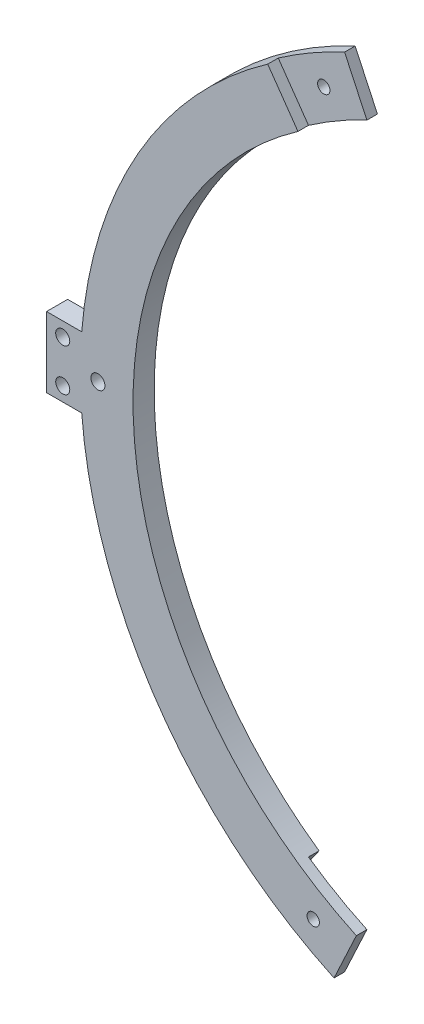
SolidWorks part; units mm, degrees
ref_plane "Plan de face" through (0, 0, 0) normal (0, 0, 1) x (1, 0, 0)
ref_plane "Plan de dessus" through (0, 0, 0) normal (0, 1, 0) x (1, 0, 0)
ref_plane "Plan de droite" through (0, 0, 0) normal (1, 0, 0) x (0, 0, -1)
sketch "Esquisse1" plane through (0, 0, 0) normal (0, 0, 1) x (1, 0, 0)
  line L0 (-130, -6) -> (-130, 6) construction
  line L1 (-120, 0) -> (-130, 0) construction
  line L2 (-134.5994, -10) -> (-124.5994, -10)
  line L3 (-124.5994, 10) -> (-134.5994, 10)
  line L4 (-134.5994, 10) -> (-134.5994, -10)
  line L5 (-124.5994, -10) -> (-124.5994, 10) construction
  line L6 (-130, 0) -> (0, 0) construction
  line L7 (-46.488, -99.6939) -> (-52.8273, -113.2885)
  line L8 (-46.488, 99.6939) -> (-52.8273, 113.2885)
  line L9 (0, 0) -> (-46.488, 99.6939) construction
  line L10 (0, 0) -> (-46.488, -99.6939) construction
  arc A0 (-52.8273, 113.2885) -> (-124.5994, 10) centre (0, 0) ccw
  arc A1 (-46.488, 99.6939) -> (-46.488, -99.6939) centre (0, 0) ccw
  arc A2 (-124.5994, -10) -> (-52.8273, -113.2885) centre (0, 0) ccw
  circle A3 centre (-120, 0) radius 2
  circle A4 centre (-130, 6) radius 2
  circle A5 centre (-130, -6) radius 2
  dimension "D4" = 4
  dimension "D5" = 125
  dimension "D6" = 110
  dimension "D1" = 120
  dimension "D2" = 12
  dimension "D3" = 10
  dimension "D7" = 65
  dimension "D8" = 65
  dimension "D9" = 20
  dimension "D10" = 10
extrude "Boss.-Extru.1" add sketch "Esquisse1" along normal blind 6
sketch "Esquisse3" plane through (0, 0, 6) normal (0, 0, 1) x (1, 0, 0)
  line L0 (-58.75, 101.758) -> (0, 0) construction
  line L1 (0, 0) -> (-58.75, -101.758) construction
  line L2 (0, 0) -> (-120, 0) construction
  circle A0 centre (-58.75, 101.758) radius 1.75
  circle A1 centre (-58.75, -101.758) radius 1.75
  circle A2 centre (-120, 0) radius 2 construction
  dimension "D1" = 3.5
  dimension "D2" = 120
  dimension "D3" = 60
  dimension "D4" = 117.5
extrude "Enlèv. mat.-Extru.1" cut sketch "Esquisse3" against normal blind 10
sketch "Esquisse4" plane through (0, 0, 6) normal (0, 0, 1) x (1, 0, 0)
  line L0 (-71.6971, 102.394) -> (-63.0934, 90.1067)
  line L1 (-52.8273, 113.2885) -> (-46.488, 99.6939)
  line L2 (-46.488, 99.6939) -> (-52.8273, 113.2885) construction
  line L3 (-63.0934, 90.1067) -> (0, 0) construction
  arc A0 (-46.488, 99.6939) -> (-63.0934, 90.1067) centre (0, 0) ccw
  arc A1 (-71.6971, 102.394) -> (-52.8273, 113.2885) centre (0, 0) cw
  arc A2 (-52.8273, 113.2885) -> (-124.5994, 10) centre (0, 0) ccw construction
  dimension "D1" = 10
extrude "Enlèv. mat.-Extru.2" cut sketch "Esquisse4" against normal blind 3
sketch "Esquisse6" plane through (0, 0, 0) normal (0, 0, -1) x (-1, 0, 0)
  line L0 (63.0934, -90.1067) -> (71.6971, -102.394)
  line L1 (46.488, -99.6939) -> (52.8273, -113.2885)
  line L2 (52.8273, -113.2885) -> (46.488, -99.6939) construction
  line L3 (63.0934, -90.1067) -> (0, 0) construction
  arc A0 (63.0934, -90.1067) -> (46.488, -99.6939) centre (0, 0) cw
  arc A1 (71.6971, -102.394) -> (52.8273, -113.2885) centre (0, 0) cw
  dimension "D1" = 10
extrude "Enlèv. mat.-Extru.3" cut sketch "Esquisse6" against normal blind 3
